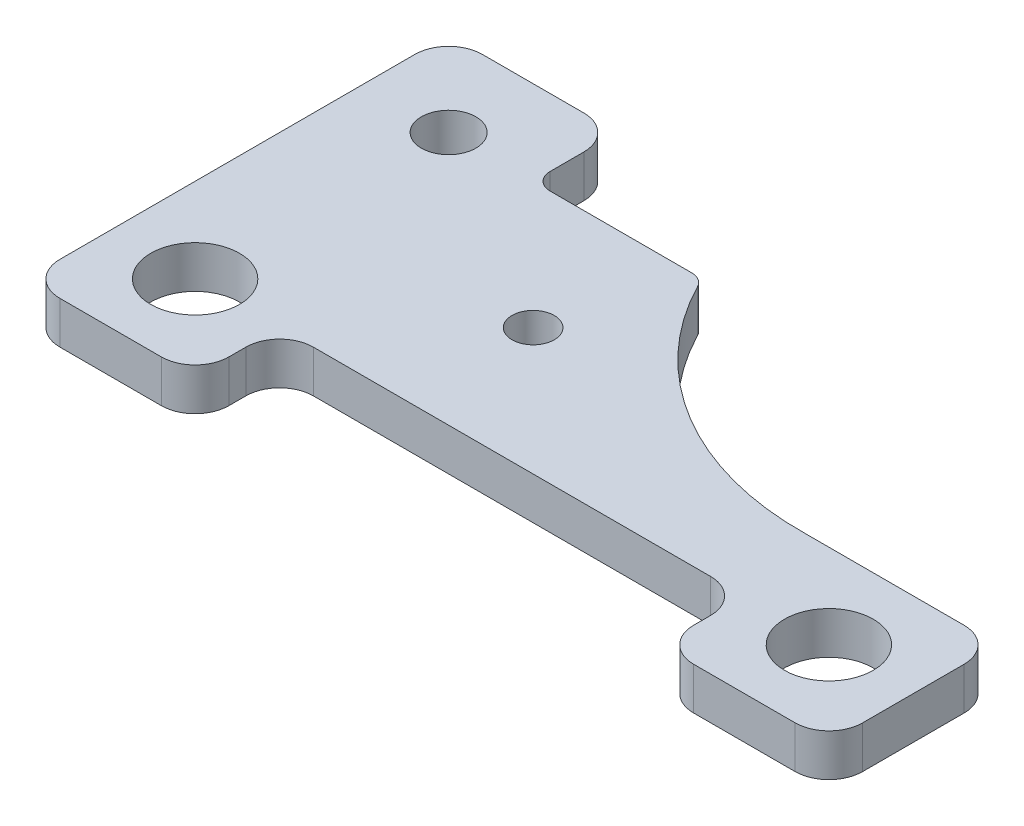
SolidWorks part; units mm, degrees
ref_plane "Front Plane" through (0, 0, 0) normal (0, 0, 1) x (1, 0, 0)
ref_plane "Top Plane" through (0, 0, 0) normal (0, 1, 0) x (1, 0, 0)
ref_plane "Right Plane" through (0, 0, 0) normal (1, 0, 0) x (0, 0, -1)
sketch "Sketch1" plane through (0, 0, 0) normal (0, 1, 0) x (1, 0, 0)
  line L0 (0, -4) -> (0, -46)
  line L1 (4, -50) -> (16, -50)
  line L2 (20, -46) -> (20, -44)
  line L3 (24, -40) -> (71, -40)
  line L4 (75, -44) -> (75, -46)
  line L5 (79, -50) -> (91, -50)
  line L6 (95, -46) -> (95, -34)
  line L7 (4, 0) -> (16, 0)
  line L8 (20, -4) -> (20, -8)
  line L9 (22, -10) -> (38.7592, -10)
  line L10 (91, -30) -> (71, -30)
  circle A1 centre (10, -40) radius 5.25
  circle A2 centre (85, -40) radius 5.25
  arc A3 (95, -34) -> (91, -30) centre (91, -34) ccw
  arc A4 (91, -50) -> (95, -46) centre (91, -46) ccw
  arc A5 (16, 0) -> (20, -4) centre (16, -4) cw
  arc A6 (0, -4) -> (4, 0) centre (4, -4) cw
  arc A7 (0, -46) -> (4, -50) centre (4, -46) ccw
  arc A8 (75, -46) -> (79, -50) centre (79, -46) ccw
  arc A9 (71, -40) -> (75, -44) centre (71, -44) cw
  arc A10 (16, -50) -> (20, -46) centre (16, -46) ccw
  arc A11 (20, -44) -> (24, -40) centre (24, -44) cw
  arc A13 (40.5357, -11.0814) -> (72.2509, -30) centre (71.6254, 4.9944) ccw
  arc A14 (20, -8) -> (22, -10) centre (22, -8) ccw
  arc A15 (38.7592, -10) -> (40.5357, -11.0814) centre (38.7592, -12) cw
  circle A16 centre (10, -10) radius 3.225
  circle A17 centre (35, -25) radius 2.5
  point P20 (95, -30)
  point P23 (95, -50)
  point P26 (20, 0)
  point P29 (0, 0)
  point P32 (0, -50)
  point P35 (75, -50)
  point P38 (75, -40)
  point P41 (20, -50)
  point P44 (20, -40)
  point P48 (20, -10)
  point P51 (40, -10)
  point P58 (-19.245, -0.7555)
  dimension "D1" = 50
  dimension "D10" = 10.5
  dimension "D15" = 10.5
  dimension "D16" = 4
  dimension "D17" = 70
  dimension "D20" = 2
  dimension "D21" = 10
  dimension "D23" = 6.45
  dimension "D26" = 5
  dimension "D2" = 20
  dimension "D3" = 20
  dimension "D4" = 10
  dimension "D5" = 20
  dimension "D6" = 10
  dimension "D7" = 55
  dimension "D8" = 20
  dimension "D9" = 20
  dimension "D11" = 10
  dimension "D12" = 10
  dimension "D13" = 10
  dimension "D14" = 10
  dimension "D18" = 20
  dimension "D19" = 10
  dimension "D22" = 10
  dimension "D24" = 15
  dimension "D25" = 25
extrude "Boss-Extrude1" add sketch "Sketch1" along normal blind 5 contours A15 L9 A14 L8 A5 L7 A6 L0 A7 L1 A10 L2 A11 L3 A9 L4 A8 L5 A4 L6 A3 L10 A13 A17 A16 A2 A1
